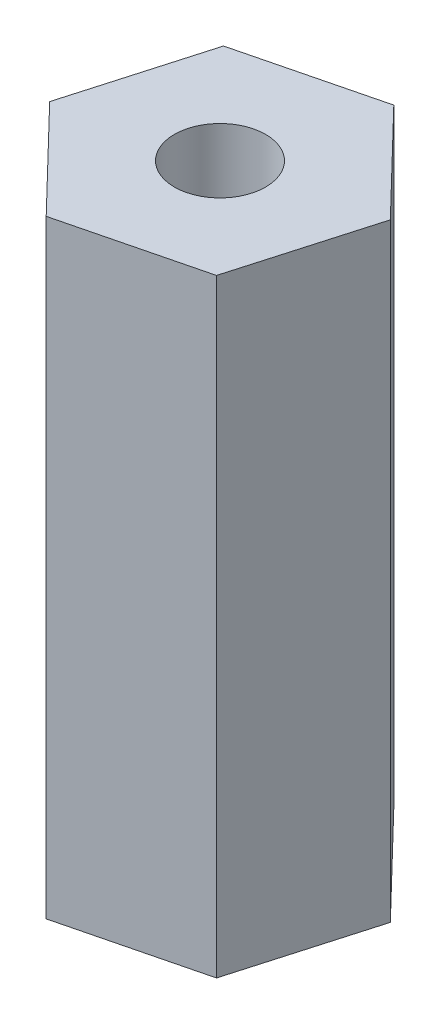
SolidWorks part; units mm, degrees
material "ABS"
ref_plane "Plano frontal" through (0, 0, 0) normal (0, 0, 1) x (1, 0, 0)
ref_plane "Plano superior" through (0, 0, 0) normal (0, 1, 0) x (1, 0, 0)
ref_plane "Plano direito" through (0, 0, 0) normal (1, 0, 0) x (0, 0, -1)
sketch "Esboço1" plane through (0, 0, 0) normal (0, 1, 0) x (1, 0, 0)
  line L1 (3.2082, -3.3228) -> (4.4817, 1.117)
  line L2 (4.4817, 1.117) -> (1.2735, 4.4398)
  line L3 (1.2735, 4.4398) -> (-3.2082, 3.3228)
  line L4 (-3.2082, 3.3228) -> (-4.4817, -1.117)
  line L5 (-4.4817, -1.117) -> (-1.2735, -4.4398)
  line L6 (-1.2735, -4.4398) -> (3.2082, -3.3228)
  circle A0 centre (0, 0) radius 4 construction
extrude "Ressalto-extrusão1" add sketch "Esboço1" along normal blind 20
sketch "Esboço2" plane through (0, 0, 0) normal (0, -1, 0) x (1, 0, 0)
  circle A0 centre (0, 0) radius 1.5
extrude "Corte-extrusão1" cut sketch "Esboço2" against normal blind 30
